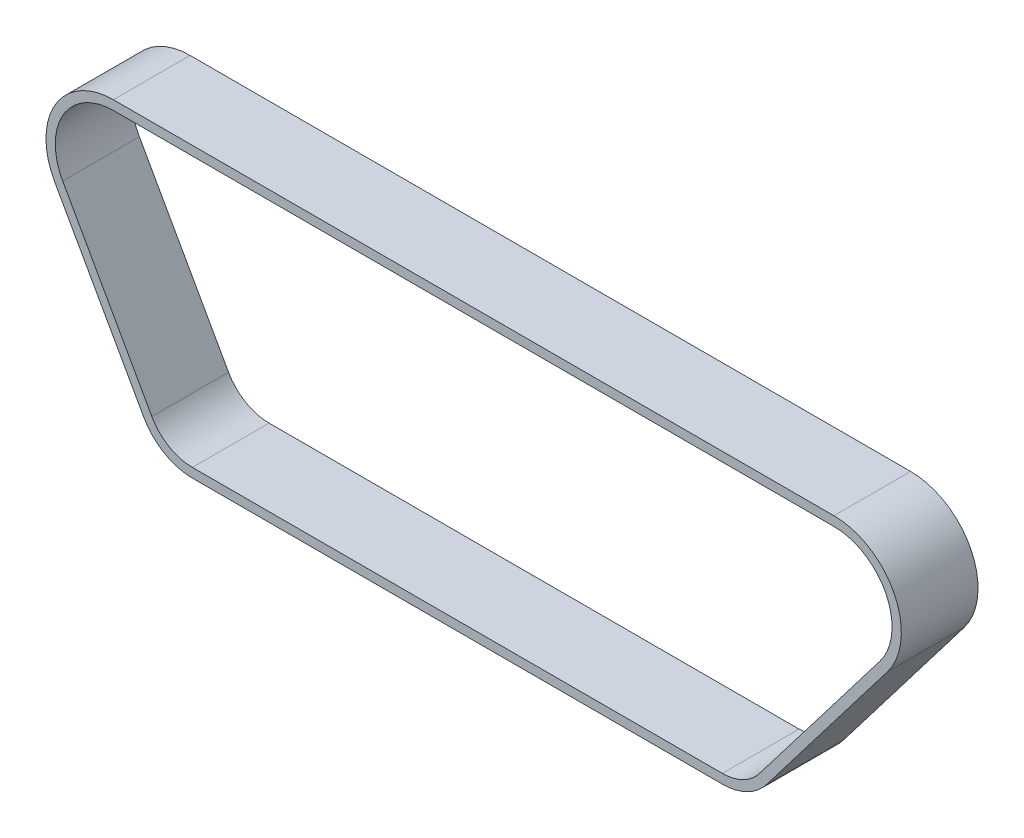
SolidWorks part; units mm, degrees
ref_plane "Front Plane" through (0, 0, 0) normal (0, 0, 1) x (1, 0, 0)
ref_plane "Top Plane" through (0, 0, 0) normal (0, 1, 0) x (1, 0, 0)
ref_plane "Right Plane" through (0, 0, 0) normal (1, 0, 0) x (0, 0, -1)
sketch "Sketch1" plane through (0, 0, 0) normal (0, 0, 1) x (1, 0, 0)
  line L0 (-155, 12.5) -> (0, 12.5)
  line L1 (9.9295, -7.5932) -> (-16.0564, -41.5745)
  line L2 (-165.9083, -6.104) -> (-146.7267, -40.3832)
  line L3 (-138, -45.5) -> (-24, -45.5)
  line L4 (-138, -47.5) -> (-24, -47.5)
  line L5 (11.5182, -8.8081) -> (-14.4677, -42.7894)
  line L6 (-155, 14.5) -> (0, 14.5)
  line L7 (-167.6536, -7.0806) -> (-148.472, -41.3598)
  circle A0 centre (-155, 0) radius 12.5 construction
  arc A1 (-155, 12.5) -> (-165.9083, -6.104) centre (-155, 0) ccw
  circle A2 centre (0, 0) radius 12.5 construction
  arc A3 (9.9295, -7.5932) -> (0, 12.5) centre (0, 0) ccw
  circle A6 centre (-138, -35.5) radius 10 construction
  arc A7 (-146.7267, -40.3832) -> (-138, -45.5) centre (-138, -35.5) ccw
  arc A8 (-24, -47.5) -> (-14.4677, -42.7894) centre (-24, -35.5) ccw
  arc A9 (11.5182, -8.8081) -> (0, 14.5) centre (0, 0) ccw
  arc A10 (-155, 14.5) -> (-167.6536, -7.0806) centre (-155, 0) ccw
  arc A11 (-148.472, -41.3598) -> (-138, -47.5) centre (-138, -35.5) ccw
  arc A12 (-24, -45.5) -> (-16.0564, -41.5745) centre (-24, -35.5) ccw construction
  circle A13 centre (-24, -35.5) radius 10 construction
  arc A14 (-24, -45.5) -> (-16.0564, -41.5745) centre (-24, -35.5) ccw
  point P29 (-24, -45.5)
  dimension "D1" = 2
extrude "Boss-Extrude1" add sketch "Sketch1" along normal mid plane 16.5
